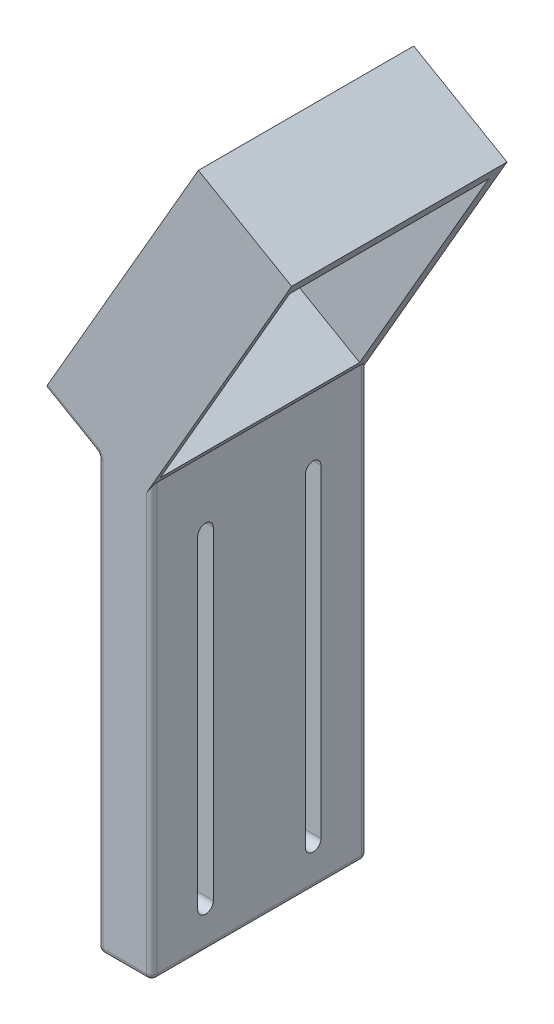
SolidWorks part; units mm, degrees
ref_plane "Plan de face" through (0, 0, 0) normal (0, 0, 1) x (1, 0, 0)
ref_plane "Plan de dessus" through (0, 0, 0) normal (0, 1, 0) x (1, 0, 0)
ref_plane "Plan de droite" through (0, 0, 0) normal (1, 0, 0) x (0, 0, -1)
sketch "Esquisse1" plane through (0, 0, 0) normal (0, 0, 1) x (1, 0, 0)
  line L1 (0, 0) -> (10, 0)
  line L6 (10, 80) -> (10, 0)
  line L7 (0, 0) -> (0, 80)
  line L11 (10, 80) -> (36, 125.0333)
  line L12 (36, 125.0333) -> (18.6795, 135.0333)
  line L13 (18.6795, 135.0333) -> (-9.8205, 85.6699)
  line L14 (-9.8205, 85.6699) -> (0, 80)
  dimension "D1" = 80
  dimension "D2" = 80
  dimension "D3" = 10
  dimension "D4" = 20
  dimension "D5" = 52
  dimension "D6" = 150
extrude "Boss.-Extru.1" add sketch "Esquisse1" along normal blind 40
fillet "Congé2" radius 1 11 edges at (5, 0, 40) (10, 0, 20) (5, 0, 0) (10, 40, 0) (10, 40, 40) (0, 40, 40) (0, 0, 20) (0, 40, 0) (-4.9103, 82.8349, 40) (-4.9103, 82.8349, 0) (0, 80, 20)
sketch "Esquisse13" plane through (0, 0, 0) normal (-1, 0, 0) x (0, 0, 1)
  line L0 (10, 7.5) -> (10, 67.5) construction
  line L1 (8.55, 7.5) -> (8.55, 67.5)
  line L2 (11.45, 7.5) -> (11.45, 67.5)
  line L3 (30, 7.5) -> (30, 67.5) construction
  line L4 (28.55, 7.5) -> (28.55, 67.5)
  line L5 (31.45, 7.5) -> (31.45, 67.5)
  line L6 (20, 7.5) -> (20, 1) construction
  line L7 (1, 1) -> (39, 1) construction
  line L8 (10, 7.5) -> (30, 7.5) construction
  line L9 (39, 0) -> (1, 0) construction
  arc A0 (8.55, 7.5) -> (11.45, 7.5) centre (10, 7.5) ccw
  arc A1 (11.45, 67.5) -> (8.55, 67.5) centre (10, 67.5) ccw
  arc A2 (28.55, 7.5) -> (31.45, 7.5) centre (30, 7.5) ccw
  arc A3 (31.45, 67.5) -> (28.55, 67.5) centre (30, 67.5) ccw
  point P2 (10, 37.5)
  point P7 (30, 37.5)
  dimension "D1" = 2.9
  dimension "2.9" = 2.9
  dimension "D2" = 20
  dimension "D3" = 60
  dimension "D4" = 7.5
extrude "Enlèv. mat.-Extru.4" cut sketch "Esquisse13" against normal up to next
sketch "Esquisse14" plane through (-44.4615, 25.6699, 0) normal (-0.866, 0.5, 0) x (0, 0, 1)
  line L0 (0, 126.282) -> (0, 70.282) construction
  line L1 (2, 75.5556) -> (39, 75.5556)
  line L2 (2, 75.5556) -> (2, 123.5556)
  line L3 (2, 123.5556) -> (39, 123.5556)
  line L4 (39, 75.5556) -> (39, 123.5556)
  dimension "D1" = 48
  dimension "D2" = 37
  dimension "D3" = 2
extrude "Enlèv. mat.-Extru.5" cut sketch "Esquisse14" against normal blind 20
